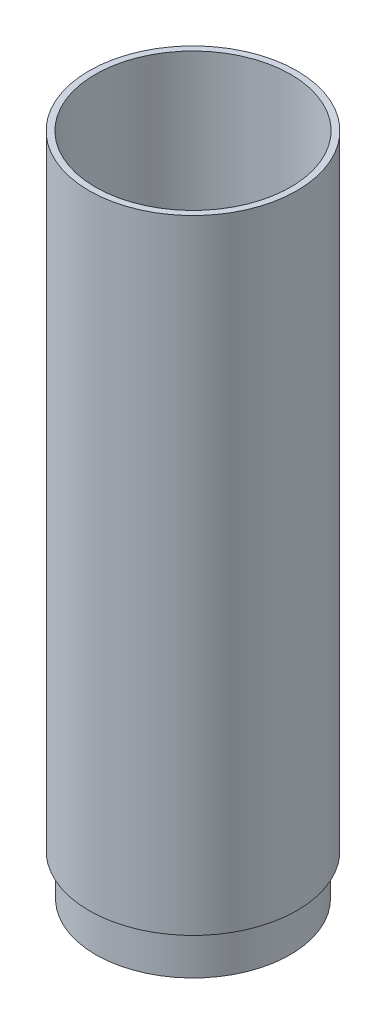
SolidWorks part; units mm, degrees
ref_plane "Plan de face" through (0, 0, 0) normal (0, 0, 1) x (1, 0, 0)
ref_plane "Plan de dessus" through (0, 0, 0) normal (0, 1, 0) x (1, 0, 0)
ref_plane "Plan de droite" through (0, 0, 0) normal (1, 0, 0) x (0, 0, -1)
sketch "Esquisse1" plane through (0, 0, 0) normal (0, 1, 0) x (1, 0, 0)
  circle A0 centre (0, 0) radius 25
  circle A1 centre (0, 0) radius 23.5
  dimension "D1" = 50
  dimension "D2" = 47
extrude "Boss.-Extru.1" add sketch "Esquisse1" along normal blind 42
sketch "Esquisse4" plane through (0, 42, 0) normal (0, 1, 0) x (1, 0, 0)
  circle A0 centre (0, 0) radius 25
  circle A1 centre (0, 0) radius 20
  dimension "D1" = 40
extrude "Boss.-Extru.4" add sketch "Esquisse4" along normal blind 3
sketch "Esquisse5" plane through (0, 45, 0) normal (0, 1, 0) x (1, 0, 0)
  circle A0 centre (0, 0) radius 25
  circle A1 centre (0, 0) radius 23.5
  circle M1 centre (0, 0) radius 25
  dimension "D1" = 47
extrude "Boss.-Extru.5" add sketch "Esquisse5" along normal blind 95 contours A1 M1
sketch "Esquisse7" plane through (0, 0, 0) normal (0, -1, 0) x (1, 0, 0)
  circle A0 centre (0, 0) radius 25
  circle A1 centre (0, 0) radius 21.5
  dimension "D1" = 43
extrude "Boss.-Extru.6" add sketch "Esquisse7" along normal blind 10
sketch "Esquisse8" plane through (0, -10, 0) normal (0, -1, 0) x (1, 0, 0)
  circle A0 centre (0, 0) radius 21.5
  circle A1 centre (0, 0) radius 23.4
  dimension "D1" = 46.8
extrude "Boss.-Extru.7" add sketch "Esquisse8" along normal blind 10
